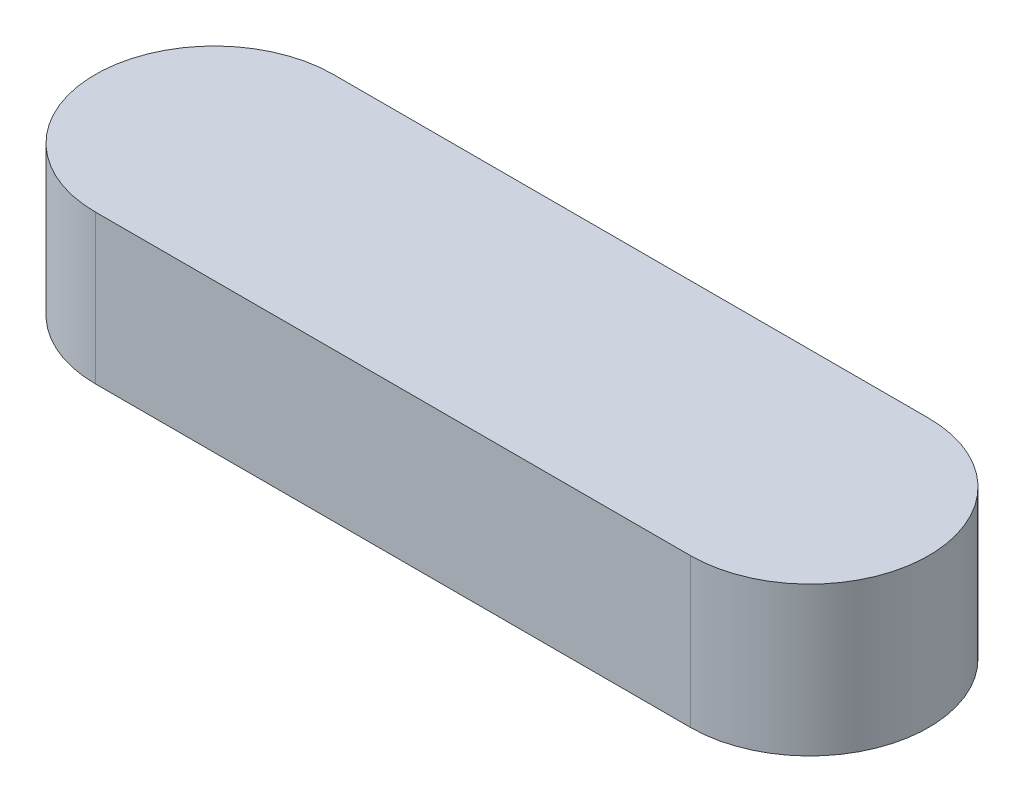
SolidWorks part; units mm, degrees
ref_plane "Front" through (0, 0, 0) normal (0, 0, 1) x (1, 0, 0)
ref_plane "Top" through (0, 0, 0) normal (0, 1, 0) x (1, 0, 0)
ref_plane "Right" through (0, 0, 0) normal (1, 0, 0) x (0, 0, -1)
sketch "support-front-body" plane through (0, 0, 0) normal (0, 0, 1) x (1, 0, 0)
  line L0 (-28, 5) -> (28, 5) construction
  line L1 (-28, 10) -> (28, 10)
  line L2 (-28, 10) -> (-28, 0)
  line L3 (-28, 0) -> (28, 0)
  line L4 (28, 10) -> (28, 0)
  line L5 (0, 10) -> (0, 0) construction
  dimension "length" = 56
  dimension "height" = 10
sketch "support-top-body" plane through (0, 0, 0) normal (0, 1, 0) x (1, 0, 0)
  line L0 (-20, 8) -> (20, 8)
  line L1 (20, -8) -> (-20, -8)
  line L2 (28, 0) -> (-28, 0) construction
  line L3 (0, 8) -> (0, -8) construction
  line L4 (-28, 0) -> (28, 0) construction
  arc A0 (20, 8) -> (20, -8) centre (20, 0) cw
  arc A1 (-20, -8) -> (-20, 8) centre (-20, 0) cw
  dimension "width" = 16
ref_plane "ref-plane-top" through (0, 10, 0) normal (0, 1, 0) x (-1, 0, 0)
sketch "Sketch4" plane through (0, 0, 0) normal (0, 1, 0) x (1, 0, 0)
  line L2 (20, 8) -> (-20, 8)
  line L3 (-20, -8) -> (20, -8)
  line L4 (20, 8) -> (-20, 8)
  line L5 (-20, -8) -> (20, -8)
  arc A2 (-20, 8) -> (-20, -8) centre (-20, 0) ccw
  arc A3 (20, -8) -> (20, 8) centre (20, 0) ccw
  arc A4 (-20, 8) -> (-20, -8) centre (-20, 0) ccw
  arc A5 (20, -8) -> (20, 8) centre (20, 0) ccw
  dimension "D1" = 0
extrude "body" add sketch "Sketch4" along normal up to surface (10 mm away) up to plane "ref-plane-top"
